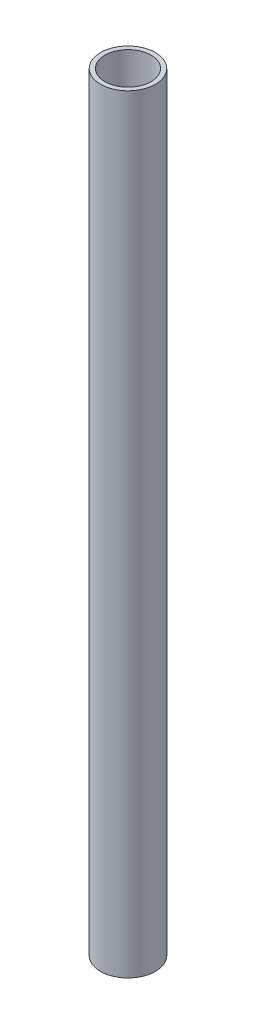
SolidWorks part; units mm, degrees
material "Thornel VCB-20 Carbon Cloth"
ref_plane "Front Plane" through (0, 0, 0) normal (0, 0, 1) x (1, 0, 0)
ref_plane "Top Plane" through (0, 0, 0) normal (0, 1, 0) x (1, 0, 0)
ref_plane "Right Plane" through (0, 0, 0) normal (1, 0, 0) x (0, 0, -1)
sketch "Sketch1" plane through (0, 0, 0) normal (0, 1, 0) x (1, 0, 0)
  circle A0 centre (0, 0) radius 12.5
  circle A1 centre (0, 0) radius 10.5
  dimension "D1" = 25
  dimension "D2" = 21
extrude "Boss-Extrude1" add sketch "Sketch1" along normal blind 350
sketch "Sketch2" [suppressed] plane through (0, 0, 0) normal (0, 0, 1) x (1, 0, 0)
  line L0 (0, 0) -> (106.9072, 0) construction
sketch "Sketch3" plane through (0, 0, 0) normal (1, 0, 0) x (0, 0, -1)
  line L0 (12.5, 350) -> (-12.5, 350) construction
  line L1 (12.5, 350) -> (-12.5, 350)
  circle A0 centre (0, 350) radius 3.3557
extrude "Boss-Extrude2" [suppressed] add sketch "Sketch3" along normal blind 18 contours A0
